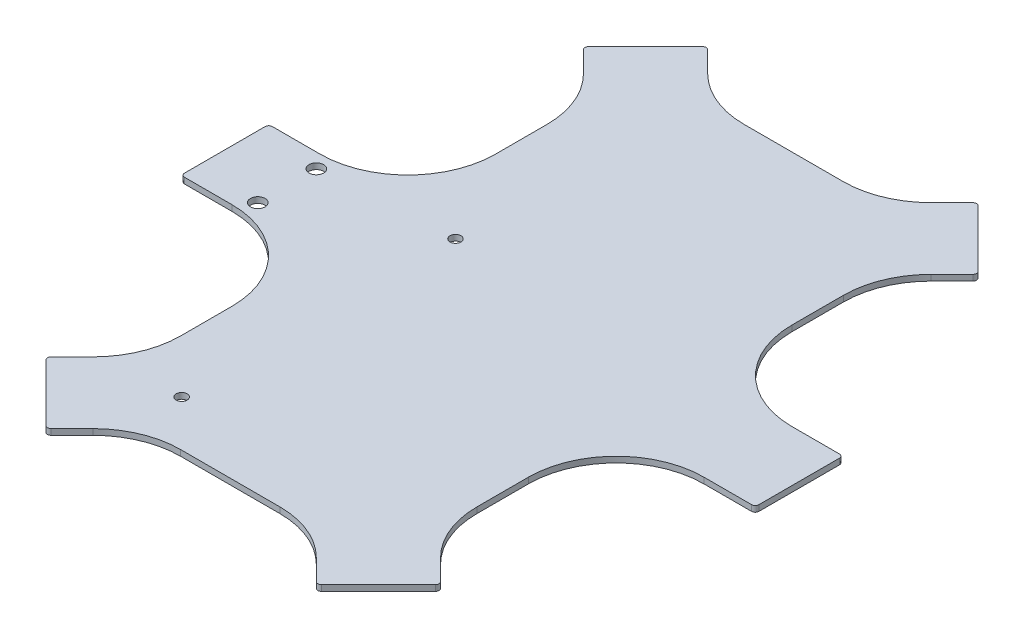
SolidWorks part; units mm, degrees
material "1060 合金"
ref_plane "前视基准面" through (0, 0, 0) normal (0, 0, 1) x (1, 0, 0)
ref_plane "上视基准面" through (0, 0, 0) normal (0, 1, 0) x (1, 0, 0)
ref_plane "右视基准面" through (0, 0, 0) normal (1, 0, 0) x (0, 0, -1)
other "Configuration Table"
sketch "草图1" [suppressed] plane through (0, 0, 0) normal (0, 1, 0) x (1, 0, 0)
  line L30 (25, 78.9) -> (40.5563, 63.3436)
  line L32 (40.5563, -46.6564) -> (25, -62.2127)
  line L33 (30.8579, 84.7578) -> (39.1421, 93.0421)
  line L34 (-16.7157, -62.2127) -> (16.7157, -62.2127)
  line L35 (0, 87.4232) -> (0, -140.4118) construction
  line L36 (40.5563, 93.0421) -> (54.6985, 78.9)
  line L37 (54.6985, 77.4858) -> (46.4142, 69.2015)
  line L38 (60.5563, 19.3436) -> (80.5563, 19.3436)
  line L39 (81.5563, 18.3436) -> (81.5563, -1.6564)
  line L40 (80.5563, -2.6564) -> (60.5563, -2.6564)
  line L41 (-52.5772, -89.7899) -> (-30.8579, -68.0706)
  line L42 (40.5563, 55.0594) -> (40.5563, 39.3436)
  line L43 (46.4142, -52.5142) -> (68.1335, -74.2335)
  line L44 (68.1335, -75.6477) -> (53.9914, -89.7899)
  line L45 (52.5772, -89.7899) -> (30.8579, -68.0706)
  line L46 (16.7157, 78.9) -> (-16.7157, 78.9)
  line L47 (-68.1335, -75.6477) -> (-53.9914, -89.7899)
  line L48 (-46.4142, -52.5142) -> (-68.1335, -74.2335)
  line L49 (-40.5563, 55.0837) -> (-40.5563, 39.3436)
  line L50 (-80.5563, -2.6564) -> (-60.5563, -2.6564)
  line L51 (-81.5563, 18.3436) -> (-81.5563, -1.6564)
  line L57 (-40.5563, 8.3436) -> (40.5563, 8.3436) construction
  line L59 (-60.5563, 19.3436) -> (-80.5563, 19.3436)
  line L67 (-54.6706, 77.5166) -> (-46.3849, 69.1964)
  line L68 (-40.5563, 93.0421) -> (-54.6691, 78.9294)
  line L69 (-30.8579, 84.7578) -> (-39.1421, 93.0421)
  line L70 (-40.5563, -46.6564) -> (-25, -62.2127)
  line L71 (-25, 78.9) -> (-40.5563, 63.3436)
  line L72 (40.5563, -22.6564) -> (40.5563, -38.3721)
  line L73 (-40.5563, -22.6564) -> (-40.5563, -38.3721)
  arc A0 (-16.7157, -62.2127) -> (-30.8579, -68.0706) centre (-16.7157, -82.2127) ccw
  arc A1 (-40.5563, -38.3721) -> (-46.4142, -52.5142) centre (-60.5563, -38.3721) cw
  arc A2 (-40.5563, -22.6564) -> (-60.5563, -2.6564) centre (-60.5563, -22.6564) ccw
  arc A3 (-40.5563, 39.3436) -> (-60.5563, 19.3436) centre (-60.5563, 39.3436) cw
  arc A4 (-46.3849, 69.1964) -> (-40.5563, 55.0837) centre (-60.5563, 55.0837) cw
  arc A5 (-30.8579, 84.7578) -> (-16.7157, 78.9) centre (-16.7157, 98.9) ccw
  arc A6 (16.7157, -62.2127) -> (30.8579, -68.0706) centre (16.7157, -82.2127) cw
  arc A7 (40.5563, -38.3721) -> (46.4142, -52.5142) centre (60.5563, -38.3721) ccw
  arc A8 (40.5563, -22.6564) -> (60.5563, -2.6564) centre (60.5563, -22.6564) cw
  arc A9 (40.5563, 39.3436) -> (60.5563, 19.3436) centre (60.5563, 39.3436) ccw
  arc A10 (40.5563, 55.0594) -> (46.4142, 69.2015) centre (60.5563, 55.0594) cw
  arc A11 (30.8579, 84.7578) -> (16.7157, 78.9) centre (16.7157, 98.9) cw
  arc A12 (-81.5563, 18.3436) -> (-80.5563, 19.3436) centre (-80.5563, 18.3436) cw
  arc A13 (-80.5563, -2.6564) -> (-81.5563, -1.6564) centre (-80.5563, -1.6564) cw
  arc A14 (-68.1335, -75.6477) -> (-68.1335, -74.2335) centre (-67.4264, -74.9406) cw
  arc A15 (-52.5772, -89.7899) -> (-53.9914, -89.7899) centre (-53.2843, -89.0828) cw
  arc A16 (68.1335, -74.2335) -> (68.1335, -75.6477) centre (67.4264, -74.9406) cw
  arc A17 (53.9914, -89.7899) -> (52.5772, -89.7899) centre (53.2843, -89.0828) cw
  arc A18 (81.5563, -1.6564) -> (80.5563, -2.6564) centre (80.5563, -1.6564) cw
  arc A19 (80.5563, 19.3436) -> (81.5563, 18.3436) centre (80.5563, 18.3436) cw
  arc A20 (54.6985, 78.9) -> (54.6985, 77.4858) centre (53.9914, 78.1929) cw
  arc A21 (39.1421, 93.0421) -> (40.5563, 93.0421) centre (39.8492, 92.335) cw
  arc A22 (-39.1421, 93.0421) -> (-40.5563, 93.0421) centre (-39.8492, 92.335) ccw
  arc A23 (-54.6706, 77.5166) -> (-54.6691, 78.9294) centre (-53.962, 78.2223) cw
  point P18 (-40.5563, -2.6564)
  point P29 (-40.5563, 19.3436)
  point P31 (0, 78.9)
  point P55 (40.5563, -2.6564)
  point P58 (40.5563, 19.3436)
  point P67 (-81.5563, 19.3436)
  point P70 (-81.5563, -2.6564)
  point P73 (-68.8406, -74.9406)
  point P76 (-53.2843, -90.497)
  point P79 (68.8406, -74.9406)
  point P82 (53.2843, -90.497)
  point P85 (81.5563, -2.6564)
  point P88 (81.5563, 19.3436)
  dimension "D1" = 20
  dimension "D2" = 1
  dimension "D3" = 19
  dimension "D4" = 19
  dimension "D5" = 22
  dimension "D6" = 41
sketch "草图5" plane through (0, 0, 0) normal (0, 1, 0) x (1, 0, 0)
  line L0 (0.6655, 1.7957) -> (0.1696, 1.7957)
  line L1 (0.1696, 1.7955) -> (0.1696, 5.326) construction
  line L2 (0.8947, 2.0889) -> (0.1696, 2.0889)
  line L3 (0.8947, 2.0889) -> (2.0148, 1.2751)
  line L4 (2.0148, 1.2751) -> (2.0148, 1.0558)
  line L5 (2.0148, 1.0558) -> (1.2081, -0.6653)
  line L6 (1.2081, -0.6653) -> (1.8365, -2.2852)
  line L7 (1.8365, -2.2852) -> (0.7016, -3.1098)
  line L8 (0.7016, -3.1098) -> (0.1696, -3.1098)
  line L9 (2.4149, -2.4153) -> (0.9633, -3.47)
  line L10 (0.9633, -3.47) -> (0.7016, -3.1098)
  line L11 (2.4149, -2.4153) -> (1.497, -0.049)
  line L12 (1.7081, -0.5932) -> (1.2492, -0.7713)
  line L13 (2.2113, -1.8902) -> (1.7523, -2.0683)
  line L14 (0.9633, -3.47) -> (0.1696, -3.47)
  line L15 (2.0982, -2.6454) -> (1.8365, -2.2852)
  line L16 (1.7081, -1.9542) -> (1.7081, -2.3786)
  line L17 (0.9633, -3.47) -> (0.9633, -5.3331)
  line L18 (0.9633, -5.3331) -> (-0.6241, -5.3331)
  line L19 (0.9633, -4.5041) -> (0.1696, -4.5041)
  line L20 (1.4029, 4.1544) -> (0.1696, 4.1544) construction
  line L21 (3.0798, -0.1534) -> (3.0798, -3.4472) construction
  line L22 (-2.7406, -0.1534) -> (-2.7406, -3.4472) construction
  line L23 (-0.6241, -3.47) -> (-0.6241, -5.3331)
  line L24 (-0.6241, -3.47) -> (0.1696, -3.47)
  line L25 (-0.3624, -3.1098) -> (0.1696, -3.1098)
  line L26 (-1.4973, -2.2852) -> (-0.3624, -3.1098)
  line L27 (-1.3689, -1.9542) -> (-1.3689, -2.3786)
  line L28 (-0.8689, -0.6653) -> (-1.4973, -2.2852)
  line L29 (-1.3689, -0.5932) -> (-0.91, -0.7713)
  line L30 (-1.0637, 4.1544) -> (0.1696, 4.1544) construction
  line L31 (-1.6756, 1.0558) -> (-0.8689, -0.6653)
  line L32 (-1.6756, 1.2751) -> (-1.6756, 1.0558)
  line L33 (-0.5555, 2.0889) -> (-1.6756, 1.2751)
  line L34 (-0.5555, 2.0889) -> (0.1696, 2.0889)
  line L35 (-0.3263, 1.7957) -> (0.1696, 1.7957)
  line L36 (-1.759, -2.6454) -> (-1.4973, -2.2852)
  line L37 (-1.872, -1.8902) -> (-1.4131, -2.0683)
  line L38 (-2.0757, -2.4153) -> (-1.1578, -0.049)
  line L39 (-2.0757, -2.4153) -> (-0.6241, -3.47)
  line L40 (-0.6241, -4.5041) -> (0.1696, -4.5041)
  point P56 (0.1696, -5.3331)
  dimension "D1" = 144
  dimension "D2" = 144
sketch "草图6" [suppressed] plane through (0, 0, 0) normal (0, 1, 0) x (1, 0, 0)
  line L0 (-2.75, 0) -> (2.75, 0) construction
  line L1 (-54.2835, 48) -> (-88.2861, 82.0025)
  line L2 (-88.2861, 82.0025) -> (-58.5876, 111.701)
  line L3 (-58.5876, 111.701) -> (-32.4014, 85.5148)
  line L4 (-60.4337, 21) -> (-101.8, 21)
  line L5 (-101.8, 21) -> (-101.8, -21)
  line L6 (-101.8, -21) -> (-60.4337, -21)
  line L7 (-54.2835, -48) -> (-88.2861, -82.0025)
  line L8 (-58.5876, -111.701) -> (-32.4014, -85.5148)
  line L9 (-88.2861, -82.0025) -> (-58.5876, -111.701)
  line L10 (-73.4369, 96.8518) -> (-45.1526, 68.5675)
  line L11 (-101.8, 0) -> (-61.8, 0)
  line L12 (-73.4369, -96.8518) -> (-45.1526, -68.5675)
  line L13 (0, -137.0204) -> (0, 137.0204) construction
  ellipse E0 centre (0, 0) end of major axis (0, 100.4241) minor radius 61.8
  dimension "D1" = 48
  dimension "D2" = 24
  dimension "D3" = 45
  dimension "D4" = 24
  dimension "D5" = 12
  dimension "D6" = 19
  dimension "D7" = 40
  dimension "D8" = 73.4369
  dimension "D9" = 96.8518
sketch "草图7" [suppressed] plane through (0, 0, 0) normal (0, 0, 1) x (1, 0, 0)
  line L0 (32.3745, -44.4151) -> (32.3981, -38.3402)
  line L2 (10.7336, -68.0209) -> (32.3745, -44.4151)
  line L3 (0, -68.0206) -> (10.7336, -68.0209)
  line L8 (32.3981, -38.3402) -> (17.3573, 0)
  line L10 (-17.3573, 0) -> (17.3573, 0)
  line L20 (35.7261, 42.3907) -> (35.6862, 45.8735)
  line L21 (17.3918, 3.5) -> (35.7261, 42.3907)
  line L22 (-17.3918, 3.5) -> (17.3918, 3.5)
  line L28 (12.7226, 62.5615) -> (-12.7226, 62.5615)
  line L29 (35.6862, 45.8735) -> (12.7226, 62.5615)
  line L30 (25, 80.3142) -> (41.9706, 63.3436)
  line L32 (41.9706, -46.6564) -> (25, -63.6269)
  line L33 (25, 80.3142) -> (53.2843, 108.5985)
  line L34 (-25, -63.6269) -> (25, -63.6269)
  line L35 (0, 87.4232) -> (0, -140.4118) construction
  line L36 (53.2843, 108.5985) -> (70.2548, 91.6279)
  line L37 (70.2548, 91.6279) -> (41.9706, 63.3436)
  line L38 (41.9706, 20.3436) -> (81.9706, 20.3436)
  line L39 (81.9706, 20.3436) -> (81.9706, -3.6564)
  line L40 (81.9706, -3.6564) -> (41.9706, -3.6564)
  line L41 (-53.2843, -91.9112) -> (-25, -63.6269)
  line L42 (41.9706, 63.3436) -> (41.9706, -46.6564)
  line L43 (41.9706, -46.6564) -> (70.2548, -74.9406)
  line L44 (70.2548, -74.9406) -> (53.2843, -91.9112)
  line L45 (53.2843, -91.9112) -> (25, -63.6269)
  line L46 (25, 80.3142) -> (-25, 80.3142)
  line L47 (-70.2548, -74.9406) -> (-53.2843, -91.9112)
  line L48 (-41.9706, -46.6564) -> (-70.2548, -74.9406)
  line L49 (-41.9706, 63.3436) -> (-41.9706, -46.6564)
  line L50 (-81.9706, -3.6564) -> (-41.9706, -3.6564)
  line L51 (-81.9706, 20.3436) -> (-81.9706, -3.6564)
  line L57 (-41.9706, 8.3436) -> (41.9706, 8.3436) construction
  line L59 (-41.9706, 20.3436) -> (-81.9706, 20.3436)
  line L66 (0, -68.0206) -> (-10.7336, -68.0209)
  line L67 (-70.2548, 91.7457) -> (-41.9706, 63.3436)
  line L68 (-53.3432, 108.6574) -> (-70.2548, 91.7457)
  line L69 (-25, 80.3142) -> (-53.3432, 108.6574)
  line L70 (-41.9706, -46.6564) -> (-25, -63.6269)
  line L71 (-25, 80.3142) -> (-41.9706, 63.3436)
  line L72 (-35.6862, 45.8735) -> (-12.7226, 62.5615)
  line L73 (-17.3918, 3.5) -> (-35.7261, 42.3907)
  line L74 (-35.7261, 42.3907) -> (-35.6862, 45.8735)
  line L75 (-32.3981, -38.3402) -> (-17.3573, 0)
  line L76 (-10.7336, -68.0209) -> (-32.3745, -44.4151)
  line L77 (-32.3745, -44.4151) -> (-32.3981, -38.3402)
  point P31 (0, 80.3142)
  point P45 (0, 62.5615)
  point P46 (0, 3.5)
  point P48 (0, 0)
  dimension "D1" = 24
  dimension "D2" = 24
  dimension "D3" = 135
  dimension "D4" = 12
  dimension "D5" = 40
  dimension "D6" = 110
  dimension "D7" = 40
  dimension "D8" = 24
  dimension "D9" = 50
  dimension "D11" = 40
sketch "草图8" plane through (0, 0, 0) normal (0, -1, 0) x (1, 0, 0)
  line L30 (23.5, 76.9706) -> (40.4706, 60)
  line L32 (40.4706, -60) -> (23.5, -76.9706)
  line L33 (30.5294, 84) -> (36.2279, 89.6985)
  line L34 (-13.5589, -76.9706) -> (13.5589, -76.9706)
  line L35 (0, 87.4232) -> (0, -140.4118) construction
  line L36 (37.6421, 89.6985) -> (53.1985, 74.1421)
  line L37 (53.1985, 72.7279) -> (47.5, 67.0294)
  line L38 (64.4706, 12) -> (77.4706, 12)
  line L39 (78.4706, 11) -> (78.4706, -11)
  line L40 (77.4706, -12) -> (64.4706, -12)
  line L41 (-36.2279, -89.6985) -> (-30.5294, -84)
  line L42 (40.4706, 50.0589) -> (40.4706, 36)
  line L43 (47.5, -67.0294) -> (53.1985, -72.7279)
  line L44 (53.1985, -74.1421) -> (37.6421, -89.6985)
  line L45 (36.2279, -89.6985) -> (30.5294, -84)
  line L46 (13.5589, 76.9706) -> (-13.5589, 76.9706)
  line L47 (-53.1985, -74.1421) -> (-37.6421, -89.6985)
  line L48 (-47.5, -67.0294) -> (-53.1985, -72.7279)
  line L49 (-40.4706, 50.0589) -> (-40.4706, 36)
  line L50 (-77.4706, -12) -> (-64.4706, -12)
  line L51 (-78.4706, 11) -> (-78.4706, -11)
  line L57 (-55.7635, 0) -> (25.3492, 0) construction
  line L59 (-64.4706, 12) -> (-77.4706, 12)
  line L67 (-53.1985, 72.7279) -> (-47.5, 67.0294)
  line L68 (-37.6421, 89.6985) -> (-53.1985, 74.1421)
  line L69 (-30.5294, 84) -> (-36.2279, 89.6985)
  line L70 (-40.4706, -60) -> (-23.5, -76.9706)
  line L71 (-23.5, 76.9706) -> (-40.4706, 60)
  line L72 (-40.4706, -36) -> (-40.4706, -50.0589)
  line L73 (40.4706, -36) -> (40.4706, -50.0589)
  arc A0 (-40.4706, -50.0589) -> (-47.5, -67.0294) centre (-64.4706, -50.0589) cw
  arc A1 (-13.5589, -76.9706) -> (-30.5294, -84) centre (-13.5589, -100.9706) ccw
  arc A2 (30.5294, -84) -> (13.5589, -76.9706) centre (13.5589, -100.9706) ccw
  arc A3 (47.5, -67.0294) -> (40.4706, -50.0589) centre (64.4706, -50.0589) cw
  arc A4 (64.4706, -12) -> (40.4706, -36) centre (64.4706, -36) ccw
  arc A5 (-64.4706, -12) -> (-40.4706, -36) centre (-64.4706, -36) cw
  arc A6 (-64.4706, 12) -> (-40.4706, 36) centre (-64.4706, 36) ccw
  arc A7 (40.4706, 36) -> (64.4706, 12) centre (64.4706, 36) ccw
  arc A8 (40.4706, 50.0589) -> (47.5, 67.0294) centre (64.4706, 50.0589) cw
  arc A9 (13.5589, 76.9706) -> (30.5294, 84) centre (13.5589, 100.9706) ccw
  arc A10 (-13.5589, 76.9706) -> (-30.5294, 84) centre (-13.5589, 100.9706) cw
  arc A11 (-40.4706, 50.0589) -> (-47.5, 67.0294) centre (-64.4706, 50.0589) ccw
  arc A12 (-78.4706, 11) -> (-77.4706, 12) centre (-77.4706, 11) cw
  arc A13 (-77.4706, -12) -> (-78.4706, -11) centre (-77.4706, -11) cw
  arc A14 (-53.1985, -74.1421) -> (-53.1985, -72.7279) centre (-52.4914, -73.435) cw
  arc A15 (-36.2279, -89.6985) -> (-37.6421, -89.6985) centre (-36.935, -88.9914) cw
  arc A16 (37.6421, -89.6985) -> (36.2279, -89.6985) centre (36.935, -88.9914) cw
  arc A17 (53.1985, -72.7279) -> (53.1985, -74.1421) centre (52.4914, -73.435) cw
  arc A18 (78.4706, -11) -> (77.4706, -12) centre (77.4706, -11) cw
  arc A19 (77.4706, 12) -> (78.4706, 11) centre (77.4706, 11) cw
  arc A20 (53.1985, 74.1421) -> (53.1985, 72.7279) centre (52.4914, 73.435) cw
  arc A21 (36.2279, 89.6985) -> (37.6421, 89.6985) centre (36.935, 88.9914) cw
  arc A22 (-53.1985, 72.7279) -> (-53.1985, 74.1421) centre (-52.4914, 73.435) cw
  arc A23 (-37.6421, 89.6985) -> (-36.2279, 89.6985) centre (-36.935, 88.9914) cw
  circle A25 centre (-61.4706, 8) radius 2 construction
  circle A26 centre (-25.888, -10.4468) radius 1.5 construction
  circle A28 centre (-25.888, 64.388) radius 1.5 construction
  circle A30 centre (-61.4706, -8) radius 2 construction
  circle A32 centre (-25.0355, 74.8492) radius 1
  circle A33 centre (-25.0355, 74.8492) radius 1
  circle A34 centre (-36.3492, 63.5355) radius 1
  circle A35 centre (-36.3492, 63.5355) radius 1
  circle A36 centre (-61.4706, 8) radius 2
  circle A37 centre (-25.888, -10.4468) radius 1.5
  circle A38 centre (-25.888, 64.388) radius 1.5
  circle A39 centre (-61.4706, -8) radius 2
  point P31 (0, 76.9706)
  point P34 (40.4706, -12)
  point P42 (-40.4706, -12)
  point P46 (-40.4706, 12)
  point P50 (40.4706, 12)
  point P68 (-78.4706, 12)
  point P71 (-78.4706, -12)
  point P74 (-53.9056, -73.435)
  point P77 (-36.935, -90.4056)
  point P80 (36.935, -90.4056)
  point P83 (53.9056, -73.435)
  point P86 (78.4706, -12)
  point P89 (78.4706, 12)
  point P92 (53.9056, 73.435)
  point P95 (36.935, 90.4056)
  dimension "D2" = 24
  dimension "D12" = 24
  dimension "D13" = 1
  dimension "D5" = 19
  dimension "D7" = 19
  dimension "D1" = 24
  dimension "D6" = 120
  dimension "D3" = 135
  dimension "D4" = 12
  dimension "D8" = 24
  dimension "D9" = 19
  dimension "D11" = 47
  dimension "D10" = 38
  dimension "D17" = 0
  dimension "D18" = 0
extrude "凸台-拉伸1" add sketch "草图8" along normal blind 1.6 contours L40 L73 L32 L34 L70 L72 L50 L51 L59 L49 L71 L46 L30 L42 L38 L39 | L48 L70 L41 L47 | L44 L45 L32 L43 | L69 L71 L67 L68 | L36 L37 L30 L33 | A35 | A33
equation "\"l\"=19"
equation "\"w\"=24"
equation "\"D2@草图6\"=\"w\""
equation "\"D4@草图6\"=\"w\""
equation "\"D5@草图6\"=\"w\"/2"
equation "\"D6@草图6\"=\"l\""
equation "\"D3@草图1\"=\"l\""
equation "\"D4@草图1\"=\"l\""
equation "\"D5@草图8\"=\"l\""
equation "\"D9@草图8\"=\"l\""
equation "\"D7@草图8\"=\"l\""
equation "\"D2@草图8\"=\"w\""
equation "\"D8@草图8\"=\"w\""
equation "\"D1@草图8\"=\"w\""
equation "\"D4@草图8\"=\"w\"/2"
